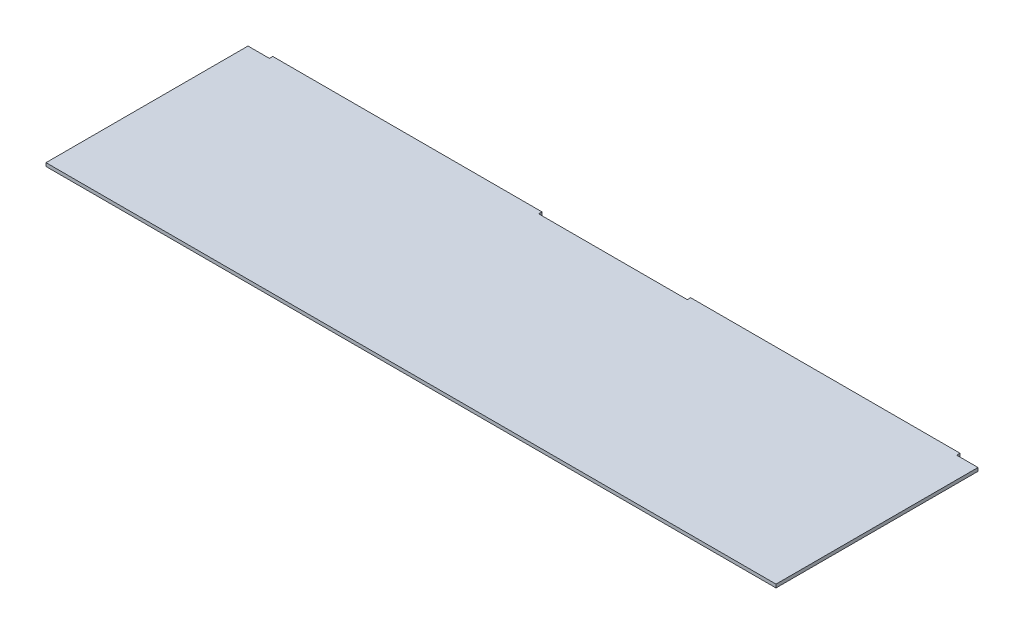
SolidWorks part; units mm, degrees
material "6061-T6 (SS)"
ref_plane "X-Y Datum" through (0, 0, 0) normal (0, 0, 1) x (1, 0, 0)
ref_plane "X-Z Datum" through (0, 0, 0) normal (0, 1, 0) x (1, 0, 0)
ref_plane "Y-Z Datum" through (0, 0, 0) normal (1, 0, 0) x (0, 0, -1)
sketch "Sketch1" plane through (0, 0, 0) normal (0, 1, 0) x (1, 0, 0)
  line L1 (-344.2208, 95.25) -> (344.2208, 95.25)
  line L2 (-344.2208, 95.25) -> (-344.2208, -95.25)
  line L3 (-344.2208, -95.25) -> (344.2208, -95.25)
  line L4 (344.2208, 95.25) -> (344.2208, -95.25)
  line L5 (-344.2208, 95.25) -> (344.2208, -95.25) construction
  line L6 (-344.2208, -95.25) -> (344.2208, 95.25) construction
  point P0 (0, 0)
  dimension "D1" = 688.4416
  dimension "D2" = 190.5
extrude "Boss-Extrude1" add sketch "Sketch1" along normal mid plane 3.175
sketch "Sketch2" plane through (0, 0, -95.25) normal (0, 0, -1) x (-1, 0, 0)
  line L0 (-344.2208, -1.5875) -> (344.2208, -1.5875) construction
  line L1 (-324.0659, -1.5875) -> (-70.0659, -1.5875)
  line L2 (-324.0659, -1.5875) -> (-324.0659, 1.5875)
  line L3 (-324.0659, 1.5875) -> (-70.0659, 1.5875)
  line L4 (-70.0659, -1.5875) -> (-70.0659, 1.5875)
  line L5 (-344.2208, 1.5875) -> (344.2208, 1.5875) construction
  line L6 (0, 55) -> (0, -55) construction
  line L7 (70.0659, -1.5875) -> (70.0659, 1.5875)
  line L8 (324.0659, -1.5875) -> (324.0659, 1.5875)
  line L9 (324.0659, -1.5875) -> (70.0659, -1.5875)
  line L10 (324.0659, 1.5875) -> (70.0659, 1.5875)
extrude "Boss-Extrude2" add sketch "Sketch2" along normal blind 3.175
